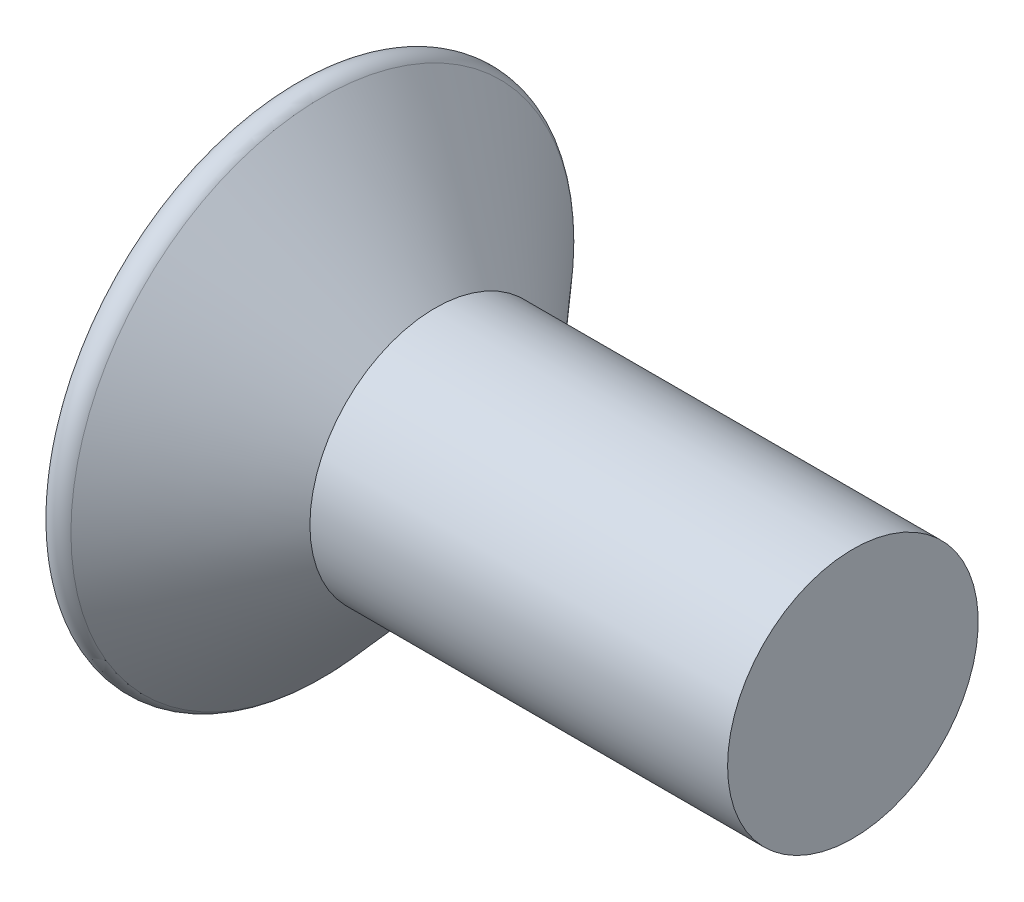
SolidWorks part; units mm, degrees
ref_plane "Plan de face" through (0, 0, 0) normal (0, 0, 1) x (1, 0, 0)
ref_plane "Plan de dessus" through (0, 0, 0) normal (0, 1, 0) x (1, 0, 0)
ref_plane "Plan de droite" through (0, 0, 0) normal (1, 0, 0) x (0, 0, -1)
sketch "Esquisse1" plane through (0, 0, 0) normal (0, 0, 1) x (1, 0, 0)
  line L0 (0, 0) -> (47.1404, 0) construction
  line L1 (0, 0) -> (0, 3.4)
  line L2 (0, 3.4) -> (1.7, 1.5)
  line L3 (1.7, 1.5) -> (6.7, 1.5)
  line L4 (6.7, 1.5) -> (6.7, 0)
  line L5 (0, 0) -> (6.7, 0)
  dimension "D1" = 3.4
  dimension "D2" = 1.7
  dimension "D3" = 1.5
  dimension "D4" = 5
revolve "Révolution1" add sketch "Esquisse1" angle 360 about L0
fillet "Congé1" radius 0.2 1 edges at (0, 0, 3.4)
sketch "Esquisse2" plane through (0, 0, 0) normal (-1, 0, 0) x (0, 0, 1)
  line L1 (0.5, -0.866) -> (1, 0)
  line L2 (1, 0) -> (0.5, 0.866)
  line L3 (0.5, 0.866) -> (-0.5, 0.866)
  line L4 (-0.5, 0.866) -> (-1, 0)
  line L5 (-1, 0) -> (-0.5, -0.866)
  line L6 (-0.5, -0.866) -> (0.5, -0.866)
  circle A0 centre (0, 0) radius 0.866 construction
  dimension "D1" = 1
extrude "Enlèv. mat.-Extru.1" cut sketch "Esquisse2" against normal blind 0.2
